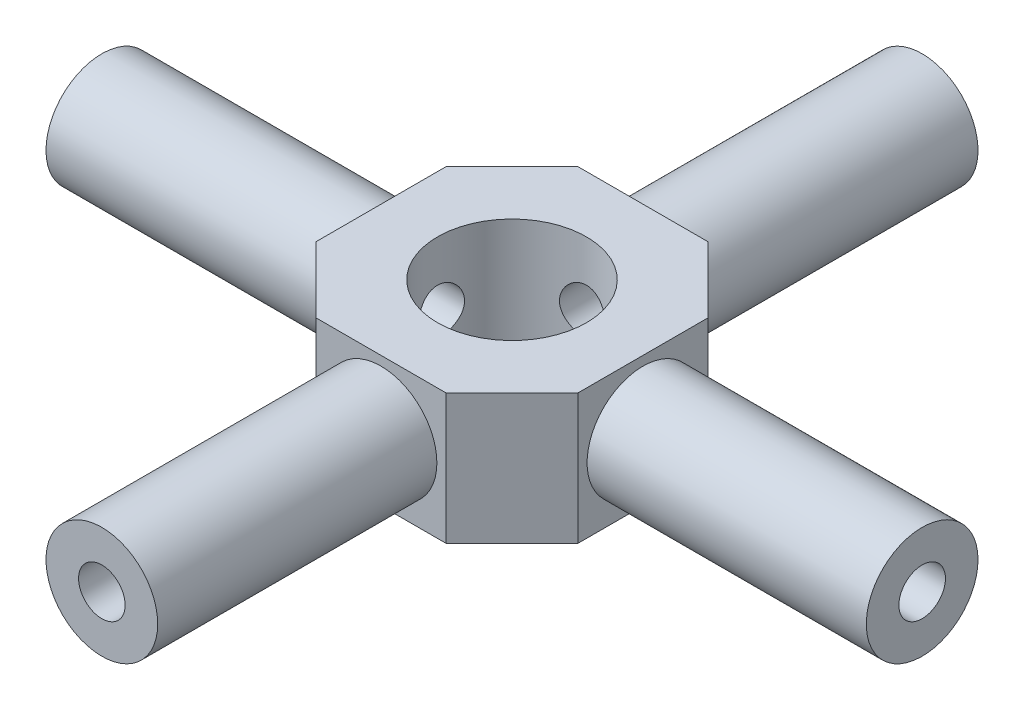
SolidWorks part; units mm, degrees
other "Quad Arm Adapter"
ref_plane "Front Plane" through (0, 0, 0) normal (0, 0, 1) x (1, 0, 0)
ref_plane "Top Plane" through (0, 0, 0) normal (0, 1, 0) x (1, 0, 0)
ref_plane "Right Plane" through (0, 0, 0) normal (1, 0, 0) x (0, 0, -1)
sketch "Sketch1" plane through (0, 0, 0) normal (0, 1, 0) x (1, 0, 0)
  line L0 (14.0711, 7) -> (14.0711, -7)
  line L1 (14.0711, -7) -> (7, -14.0711)
  line L2 (7, -14.0711) -> (-7, -14.0711)
  line L3 (-7, -14.0711) -> (-14.0711, -7)
  line L4 (-14.0711, -7) -> (-14.0711, 7)
  line L5 (-14.0711, 7) -> (-7, 14.0711)
  line L6 (-7, 14.0711) -> (7, 14.0711)
  line L7 (7, 14.0711) -> (14.0711, 7)
  point P2 (14.0711, 0)
  point P9 (0, 14.0711)
  point P11 (0, -14.0711)
  point P12 (-14.0711, 0)
  dimension "D1" = 14
  dimension "D2" = 14
  dimension "D3" = 10
extrude "Hub" add sketch "Sketch1" along normal blind 14 contours L4 L5 L6 L7 L0 L1 L2 L3
sketch "Sketch4" plane through (0, 0, 14.0711) normal (0, 0, 1) x (1, 0, 0)
  circle A0 centre (0, 7) radius 6
  point P0 (0, 7)
extrude "Arm Insert 1" add sketch "Sketch4" along normal blind 30
sketch "Sketch5" plane through (14.0711, 0, 0) normal (1, 0, 0) x (0, 0, -1)
  circle A0 centre (0, 7) radius 6
  point P0 (0, 7)
extrude "Arm Insert 2" add sketch "Sketch5" along normal blind 30
sketch "Sketch6" plane through (0, 0, -14.0711) normal (0, 0, -1) x (-1, 0, 0)
  circle A0 centre (0, 7) radius 6
  point P0 (0, 7)
extrude "Arm Insert 3" add sketch "Sketch6" along normal blind 30
sketch "Sketch7" plane through (-14.0711, 0, 0) normal (-1, 0, 0) x (0, 0, 1)
  circle A0 centre (0, 7) radius 6
  point P0 (0, 7)
extrude "Arm Insert 4" add sketch "Sketch7" along normal blind 30
sketch "Sketch8" plane through (0, 14, 0) normal (0, 1, 0) x (1, 0, 0)
  circle A0 centre (0, 0) radius 8
extrude "Hub Lightening Hole" cut sketch "Sketch8" against normal through all
sketch "Sketch9" plane through (0, 0, 44.0711) normal (0, 0, 1) x (1, 0, 0)
  circle A0 centre (0, 7) radius 2.5
extrude "Arm 1 and 3 Lightening Hole" cut sketch "Sketch9" against normal through all
sketch "Sketch10" plane through (44.0711, 0, 0) normal (1, 0, 0) x (0, 0, -1)
  circle A0 centre (0, 7) radius 2.5
extrude "Arm 2 and 4 Lightening Hole" cut sketch "Sketch10" against normal through all
